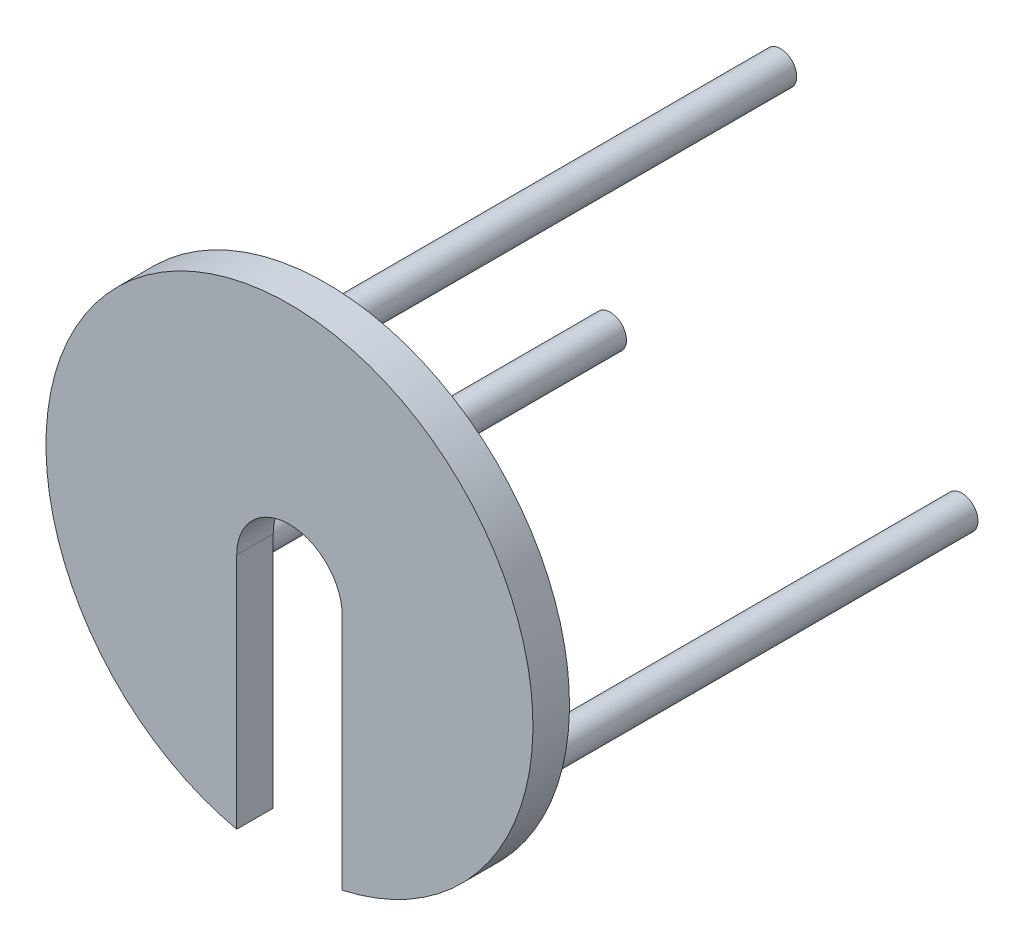
SolidWorks part; units mm, degrees
ref_plane "前视基准面" through (0, 0, 0) normal (0, 0, 1) x (1, 0, 0)
ref_plane "上视基准面" through (0, 0, 0) normal (0, 1, 0) x (1, 0, 0)
ref_plane "右视基准面" through (0, 0, 0) normal (1, 0, 0) x (0, 0, -1)
other "Configuration Table"
sketch "草图2" plane through (0, 0, 0) normal (0, 0, 1) x (1, 0, 0)
  circle A0 centre (0, 0) radius 60
  dimension "D1" = 120
extrude "凸台-拉伸1" add sketch "草图2" along normal blind 3 and the other way blind 6 contours A0
sketch "草图5" plane through (0, 0, -6) normal (0, 0, -1) x (-1, 0, 0)
  circle A0 centre (0, 50) radius 4
  dimension "D2" = 8
  dimension "D1" = 50
extrude "凸台-拉伸2" add sketch "草图5" along normal blind 112
sketch "草图6" plane through (0, 0, -6) normal (0, 0, -1) x (-1, 0, 0)
  circle A0 centre (-44.6558, -22.4913) radius 4
  circle A1 centre (41.9517, -27.204) radius 4
  dimension "D1" = 8
  dimension "D2" = 8
  dimension "D3" = 50
  dimension "D4" = 50
extrude "凸台-拉伸3" add sketch "草图6" along normal blind 112 contours A0 | A1
sketch "草图7" plane through (0, 0, 3) normal (0, 0, 1) x (1, 0, 0)
  circle A0 centre (0, 0) radius 13
  dimension "D1" = 26
sketch "草图12" plane through (0, 0, 3) normal (0, 0, 1) x (1, 0, 0)
extrude "切除-拉伸2" cut sketch "草图7" against normal blind 20
sketch "草图14" plane through (0, 0, 3) normal (0, 0, 1) x (1, 0, 0)
  line L1 (-13, 0) -> (13, 0)
  line L2 (-13, 0) -> (-13, -65)
  line L3 (-13, -65) -> (13, -65)
  line L4 (13, 0) -> (13, -65)
  circle A0 centre (0, 0) radius 13 construction
  dimension "D1" = 65
  dimension "D2" = 26
extrude "切除-拉伸3" cut sketch "草图14" against normal blind 10
